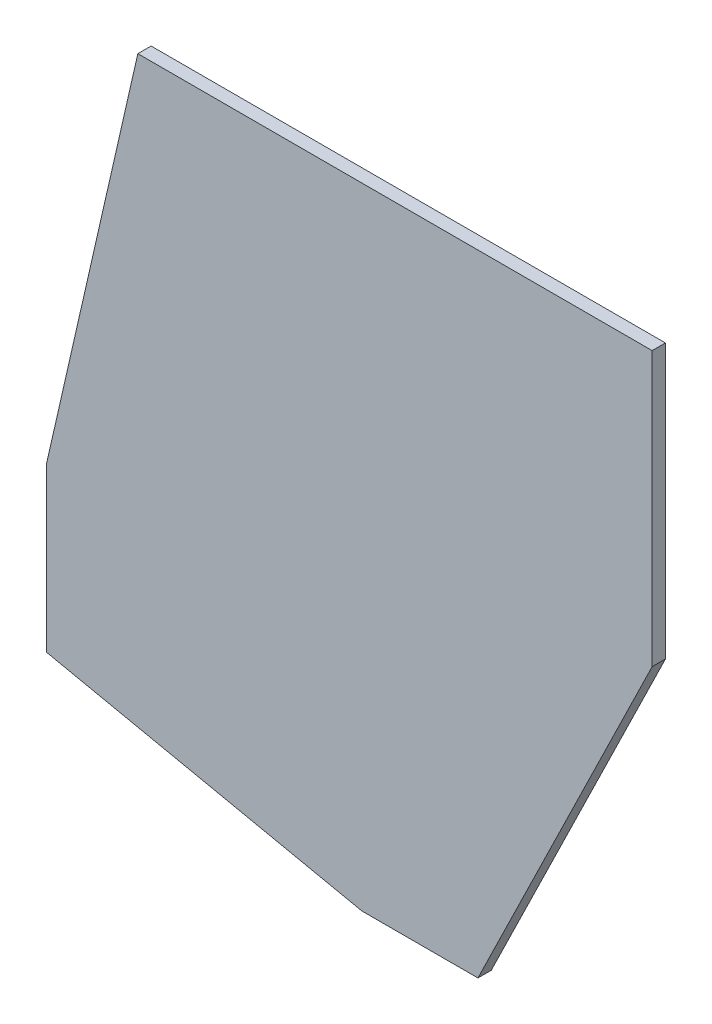
SolidWorks part; units mm, degrees
ref_plane "前视" through (0, 0, 0) normal (0, 0, 1) x (1, 0, 0)
ref_plane "上视" through (0, 0, 0) normal (0, 1, 0) x (1, 0, 0)
ref_plane "右视" through (0, 0, 0) normal (1, 0, 0) x (0, 0, -1)
sketch "草图1" plane through (0, 0, 0) normal (0, 0, 1) x (1, 0, 0)
  line L0 (730, -330) -> (520, -760)
  line L1 (110, 0) -> (730, 0)
  line L2 (0, -482.7866) -> (0, -680)
  line L3 (380, -760) -> (520, -760)
  line L4 (730, 0) -> (730, -330)
  line L5 (0, -482.7866) -> (110, 0)
  line L6 (0, 0) -> (0, 307.009) construction
  line L7 (0, 307.009) -> (0, -942.9561) construction
  line L8 (0, 0) -> (1145.1922, 0) construction
  line L9 (0, -680) -> (380, -760)
  line L10 (450, -1142.7556) -> (450, 165.6874) construction
  line L11 (510, 146.1947) -> (510, -423.4249) construction
  line L12 (-204.6726, -70) -> (986.8145, -70) construction
  line L13 (590, 146.1947) -> (590, -492.189) construction
  line L14 (-204.6726, -230) -> (918.5903, -230) construction
  line L15 (670, 146.1947) -> (670, -470.2598) construction
  line L16 (-204.6726, -150) -> (986.8145, -150) construction
  line L17 (150, 0) -> (150, -387.2631) construction
  line L18 (380, -470) -> (553.1035, -470) construction
  line L19 (250.9676, -370) -> (653.0032, -370) construction
  line L20 (380, -550) -> (553.1035, -550) construction
  line L21 (450, -400) -> (90.1534, -400) construction
  line L22 (380, -630) -> (553.1035, -630) construction
  line L23 (450, -150) -> (249.9573, -399.9658) construction
  line L24 (380, -710) -> (544.4186, -710) construction
  line L25 (249.9573, -399.9658) -> (0, -712.3029) construction
  line L26 (123.5646, -376.7449) -> (331.8306, -543.4161) construction
  line L29 (-53.2368, -650.7905) -> (192.5549, -343.6585) construction
  line L30 (506, -447.511) -> (506, -741.3026) construction
  line L31 (0, -482.7866) -> (213.7577, -653.8527) construction
  point P1 (110, 0)
  point P5 (520, -760)
  point P6 (730, -330)
  point P16 (0, -680)
  point P17 (380, -760)
  dimension "D1" = 760
  dimension "D2" = 730
  dimension "D3" = 210
  dimension "D4" = 430
  dimension "D5" = 110
  dimension "D7" = 80
  dimension "D8" = 380
  dimension "D9" = 280
  dimension "D10" = 60
  dimension "D11" = 80
  dimension "D12" = 80
  dimension "D13" = 70
  dimension "D14" = 80
  dimension "D15" = 80
  dimension "D17" = 300
  dimension "D18" = 140
  dimension "D19" = 100
  dimension "D20" = 80
  dimension "D21" = 80
  dimension "D22" = 80
  dimension "D29" = 80
extrude "基体-拉伸" add sketch "草图1" along normal blind 16
